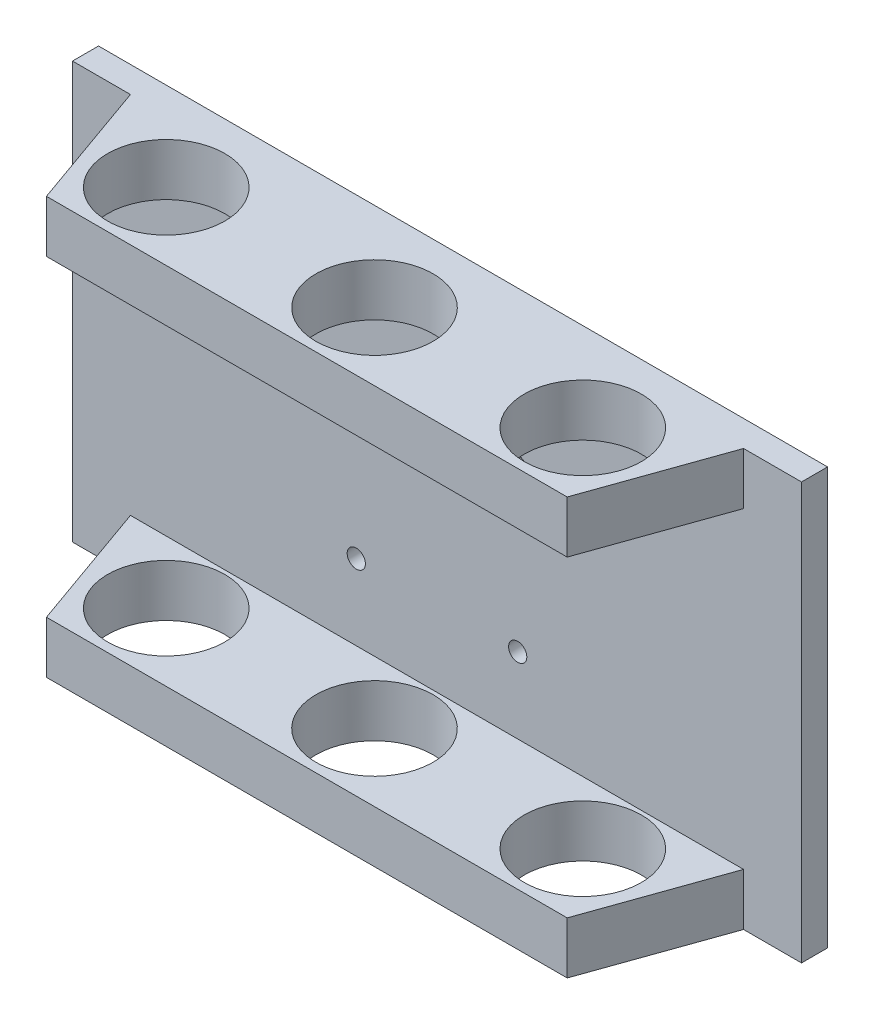
SolidWorks part; units mm, degrees
ref_plane "Спереди" through (0, 0, 0) normal (0, 0, 1) x (1, 0, 0)
ref_plane "Сверху" through (0, 0, 0) normal (0, 1, 0) x (1, 0, 0)
ref_plane "Справа" through (0, 0, 0) normal (1, 0, 0) x (0, 0, -1)
other "Configuration Table"
sketch "Эскиз1" plane through (0, 0, 0) normal (0, 1, 0) x (1, 0, 0)
  line L0 (0, 0) -> (0, -2.5) construction
  line L1 (-70, -2.5) -> (-58.8704, -2.5)
  line L2 (-70, -2.5) -> (-70, 2.5)
  line L3 (-70, 2.5) -> (70, 2.5)
  line L4 (70, -2.5) -> (70, 2.5)
  line L5 (-70, -2.5) -> (70, 2.5) construction
  line L6 (-70, 2.5) -> (70, -2.5) construction
  line L7 (0, 2.5) -> (0, -9.474) construction
  line L8 (0, -9.474) -> (0, -37.1338) construction
  line L9 (58.8704, -2.5) -> (50, -27.5)
  line L10 (50, -27.5) -> (-50, -27.5)
  line L11 (-58.8704, -2.5) -> (-50, -27.5)
  line L12 (-58.8704, -2.5) -> (0, -2.5) construction
  line L13 (58.8704, -2.5) -> (70, -2.5)
  line L14 (0, -2.5) -> (58.8704, -2.5) construction
  circle A0 centre (0, -14.5) radius 11.25
  circle A1 centre (40, -14.5) radius 11.25
  circle A2 centre (-40, -14.5) radius 11.25
  point P0 (0, 0)
  point P10 (0, -14.5)
  point P21 (0, -27.5)
  dimension "D4" = 22.5
  dimension "D1" = 140
  dimension "D2" = 5
  dimension "D3" = 12
  dimension "D6" = 250.464
  dimension "D7" = 25
  dimension "D8" = 40
  dimension "D9" = 100
  dimension "D5" = 2
extrude "Бобышка-Вытянуть1" add sketch "Эскиз1" along normal mid plane 80
sketch "Эскиз2" plane through (-70, 0, 0) normal (-1, 0, 0) x (0, 0, 1)
  line L0 (0, 0) -> (27.5, 0) construction
  line L1 (27.5, 40) -> (27.5, -40) construction
  line L2 (27.5, 0) -> (54.5347, 0) construction
  line L3 (2.5, -40) -> (27.5, -40) construction
  line L4 (2.5, 40) -> (27.5, 40) construction
  line L5 (2.5, 40) -> (2.5, -40) construction
  line L6 (2.5, -40) -> (27.5, -40) construction
  line L7 (2.5, 40) -> (27.5, 40) construction
  line L8 (27.5, 30) -> (27.5, -30)
  line L9 (2.5, 30) -> (2.5, -30)
  line L10 (2.5, 30) -> (27.5, 30)
  line L11 (27.5, 40) -> (27.5, 30) construction
  line L12 (2.5, 40) -> (2.5, 30) construction
  line L13 (2.5, -30) -> (27.5, -30)
  line L14 (2.5, -30) -> (2.5, -40) construction
  line L15 (27.5, -30) -> (27.5, -40) construction
  point P3 (2.5, 30)
  dimension "D1" = 10
extrude "Cut-Extrude1" cut sketch "Эскиз2" against normal through all
sketch "Эскиз3" plane through (0, 0, -2.5) normal (0, 0, -1) x (-1, 0, 0)
  line L1 (-15.5, 15.5) -> (15.5, 15.5) construction
  line L2 (-15.5, 15.5) -> (-15.5, -15.5) construction
  line L3 (-15.5, -15.5) -> (15.5, -15.5) construction
  line L4 (15.5, 15.5) -> (15.5, -15.5) construction
  line L5 (-15.5, 15.5) -> (15.5, -15.5) construction
  line L6 (-15.5, -15.5) -> (15.5, 15.5) construction
  circle A0 centre (-15.5, 15.5) radius 1.75
  circle A1 centre (15.5, 15.5) radius 1.75
  circle A2 centre (15.5, -15.5) radius 1.75
  circle A3 centre (-15.5, -15.5) radius 1.75
  point P0 (0, 0)
  dimension "D3" = 3.5
  dimension "D4" = 3.5
  dimension "D5" = 3.5
  dimension "D6" = 3.5
  dimension "D1" = 31
  dimension "D2" = 31
extrude "Вырез-Вытянуть1" cut sketch "Эскиз3" against normal blind 10
